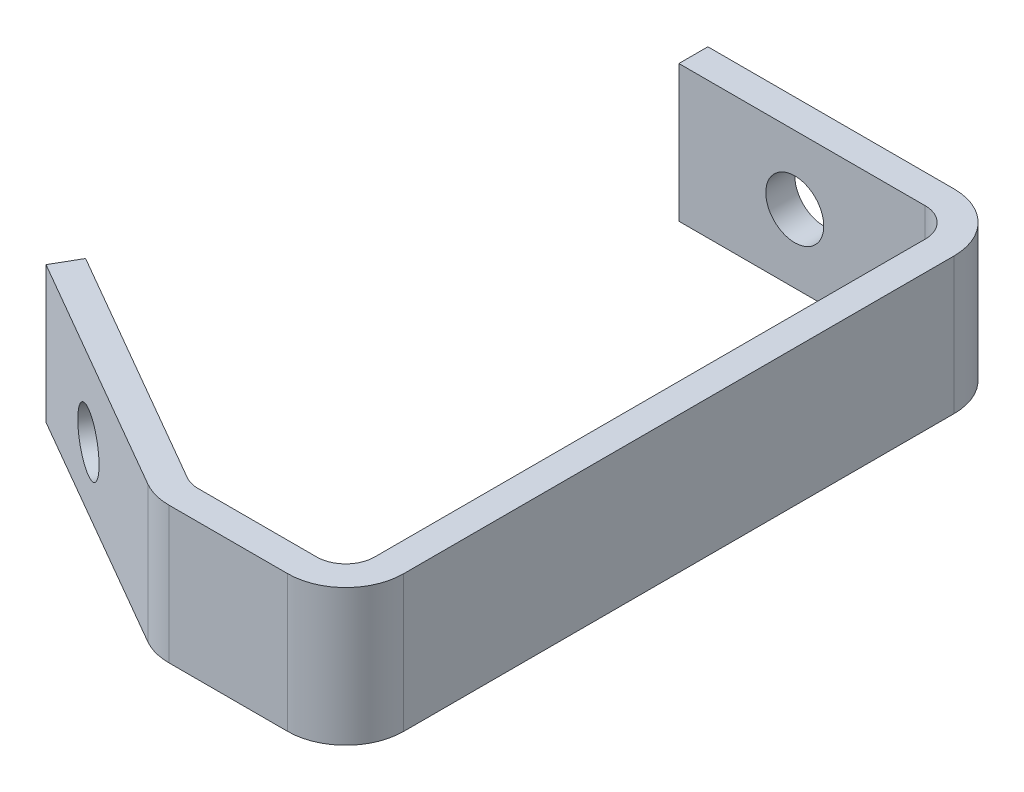
SolidWorks part; units mm, degrees
ref_plane "Front Plane" through (0, 0, 0) normal (0, 0, 1) x (1, 0, 0)
ref_plane "Top Plane" through (0, 0, 0) normal (0, 1, 0) x (1, 0, 0)
ref_plane "Right Plane" through (0, 0, 0) normal (1, 0, 0) x (0, 0, -1)
sketch "Sketch1" plane through (0, 0, 0) normal (0, 1, 0) x (1, 0, 0)
  line L0 (0, 110) -> (0, 0)
  line L1 (-50, 110) -> (0, 110)
  line L2 (0, 0) -> (-30, 0)
  line L3 (-30, 0) -> (-73.3013, 25)
  point P5 (-143.5504, 25.722)
  dimension "D1" = 50
  dimension "D2" = 110
  dimension "D3" = 30
  dimension "D4" = 50
  dimension "D5" = 150
extrude "Extrude-Thin1" add sketch "Sketch1" along normal mid plane 23.576 thin contours L1 L0 L2 L3 thin type mid plane wall 5
fillet "Fillet1" radius 5 1 edges at (-2.5, 0, -107.5)
fillet "Fillet2" radius 10 1 edges at (2.5, 0, -112.5)
fillet "Fillet3" radius 10 1 edges at (2.5, 0, 2.5)
fillet "Fillet4" radius 5 1 edges at (-2.5, 0, -2.5)
fillet "Fillet5" radius 5 1 edges at (-29.3301, 0, -2.5)
fillet "Fillet6" radius 10 1 edges at (-30.6699, 0, 2.5)
sketch "Sketch3" plane through (0, 0, -112.5) normal (0, 0, -1) x (-1, 0, 0)
  line L0 (50, 0) -> (30, 0) construction
  line L1 (50, 11.788) -> (50, -11.788) construction
  circle A0 centre (30, 0) radius 5
  dimension "D1" = 20
extrude "Cut-Extrude1" cut sketch "Sketch3" against normal blind 10 contours A0
sketch "Sketch5" plane through (-8.75, 0, 15.1554) normal (-0.5, 0, 0.866) x (0.866, 0, 0.5)
  line L0 (-75.9808, -1.7308) -> (-75.9808, -1.0766) construction
  line L1 (-75.9808, 11.788) -> (-75.9808, -11.788) construction
  line L2 (-75.9808, -1.0766) -> (-55.9808, -1.0766) construction
  circle A0 centre (-55.9808, -1.0766) radius 5
  point P7 (-161.2173, 108.3586)
extrude "Cut-Extrude2" cut sketch "Sketch5" against normal blind 10
